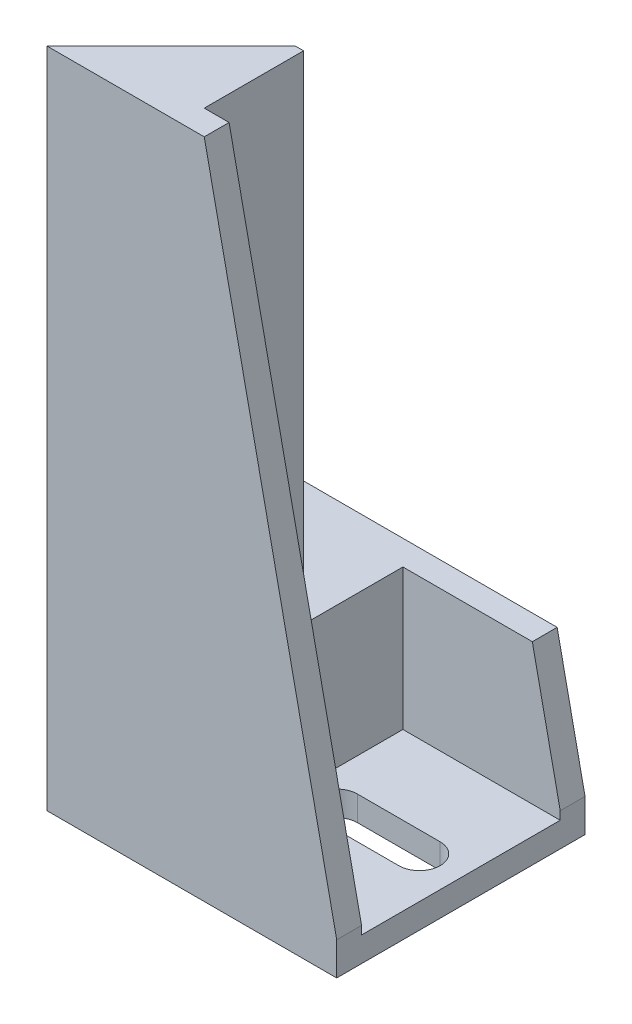
SolidWorks part; units mm, degrees
material "ABS"
ref_plane "Front Plane" through (0, 0, 0) normal (0, 0, 1) x (1, 0, 0)
ref_plane "Top Plane" through (0, 0, 0) normal (0, 1, 0) x (1, 0, 0)
ref_plane "Right Plane" through (0, 0, 0) normal (1, 0, 0) x (0, 0, -1)
sketch "Sketch1" plane through (0, 0, 0) normal (0, 0, 1) x (1, 0, 0)
  line L0 (0, 0) -> (25.4, 0)
  line L1 (25.4, 0) -> (25.4, 5.08)
  line L2 (25.4, 5.08) -> (5.08, 101.6)
  line L3 (5.08, 101.6) -> (0, 101.6)
  line L4 (0, 101.6) -> (0, 0)
  dimension "D1" = 25.4
  dimension "D2" = 5.08
  dimension "D3" = 101.6
extrude "Boss-Extrude1" add sketch "Sketch1" along normal blind 38.1
shell "Shell1" thickness 3.81
sketch "Sketch2" plane through (0, 0, 0) normal (0, -1, 0) x (1, 0, 0)
  line L0 (6.35, 19.05) -> (19.05, 19.05) construction
  line L1 (6.35, 22.225) -> (19.05, 22.225)
  line L2 (6.35, 15.875) -> (19.05, 15.875)
  line L4 (0, 38.1) -> (25.4, 38.1) construction
  line L5 (0, 38.1) -> (0, 0) construction
  arc A0 (6.35, 22.225) -> (6.35, 15.875) centre (6.35, 19.05) ccw
  arc A1 (19.05, 15.875) -> (19.05, 22.225) centre (19.05, 19.05) ccw
  point P2 (12.7, 19.05)
  point P12 (12.7, 38.1)
  point P16 (0, 19.05)
  dimension "D1" = 3.175
  dimension "D2" = 12.7
extrude "Cut-Extrude1" cut sketch "Sketch2" against normal up to surface (3.81 mm away) up to face at (12.7, 3.81, 19.05)
sketch "Sketch3" plane through (0, 101.6, 0) normal (0, 1, 0) x (1, 0, 0)
  line L0 (0, -19.05) -> (-19.05, 0)
  line L1 (0, -38.1) -> (0, 0) construction
  line L2 (-19.05, 0) -> (0, 0)
  line L3 (0, 0) -> (0, -38.1)
  line L4 (0, -38.1) -> (-19.05, -38.1)
  line L5 (-19.05, -38.1) -> (0, -19.05)
  line M5 (0, 0) -> (0, -38.1)
  dimension "D1" = 19.05
extrude "Boss-Extrude2" add sketch "Sketch3" against normal up to surface (101.6 mm away) contours L2 L0 M5 | L5 L4 M5 up to face at (12.7, 0, 19.05)
sketch "Sketch5" plane through (0, 101.6, 0) normal (0, 1, 0) x (1, 0, 0)
  line L0 (1.27, -3.81) -> (1.27, -34.29)
  line L1 (25.4, 0) -> (5.08, 0) construction
  line L3 (25.4, -3.81) -> (25.4, -34.29)
  line L4 (25.4, -38.1) -> (25.4, 0) construction
  line L5 (25.4, -34.29) -> (1.27, -34.29)
  line L6 (3.81, -34.29) -> (21.59, -34.29) construction
  line L7 (25.4, -3.81) -> (1.27, -3.81)
  dimension "D1" = 1.27
  dimension "D2" = 3.81
extrude "Cut-Extrude2" cut sketch "Sketch5" against normal up to surface (97.79 mm away) up to face at (12.7, 3.81, 25.9233)
sketch "Sketch6" plane through (0, 0, 0) normal (0, -1, 0) x (1, 0, 0)
  line L0 (-19.05, 0) -> (0, 19.05)
  line L1 (0, 19.05) -> (-19.05, 38.1)
  line L2 (-19.05, 38.1) -> (-19.05, 0)
extrude "Boss-Extrude3" add sketch "Sketch6" against normal blind 25.4
sketch "Sketch9" plane through (0, 101.6, 0) normal (0, 1, 0) x (1, 0, 0)
  line L0 (25.4, -3.81) -> (25.4, -34.29) construction
  line L1 (-19.05, 0) -> (25.4, 0)
  line L2 (-19.05, 0) -> (-19.05, -19.05)
  line L3 (-19.05, -19.05) -> (25.4, -19.05)
  line L4 (25.4, 0) -> (25.4, -19.05)
extrude "Cut-Extrude4" cut sketch "Sketch9" against normal up to surface (76.2 mm away) up to face at (-12.7, 25.4, 19.05)
